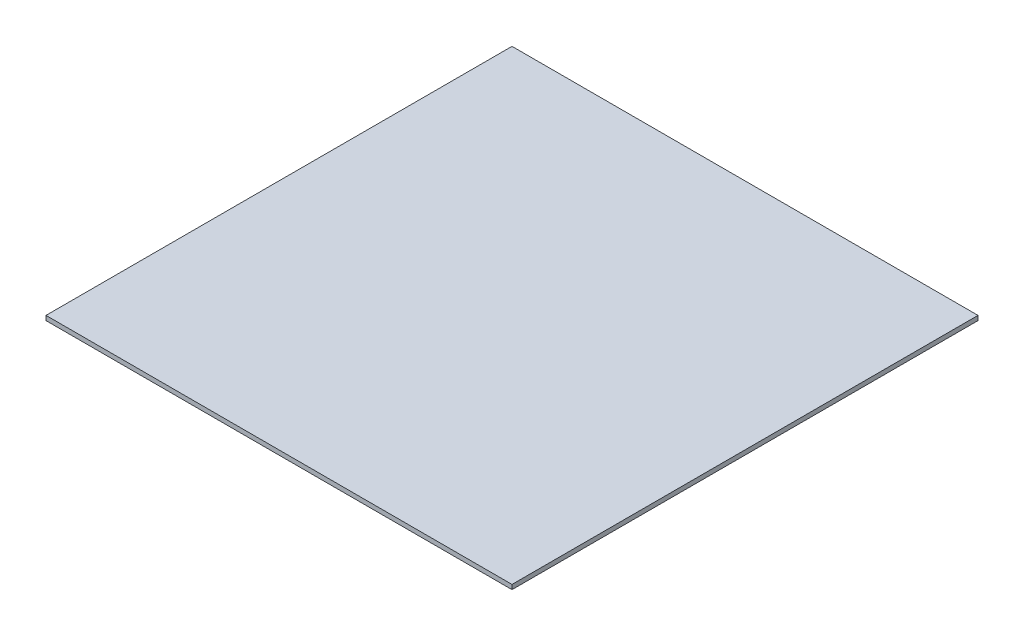
SolidWorks part; units mm, degrees
ref_plane "Front Plane" through (0, 0, 0) normal (0, 0, 1) x (1, 0, 0)
ref_plane "Top Plane" through (0, 0, 0) normal (0, 1, 0) x (1, 0, 0)
ref_plane "Right Plane" through (0, 0, 0) normal (1, 0, 0) x (0, 0, -1)
sketch "Sketch1" plane through (0, 0, 0) normal (0, 1, 0) x (1, 0, 0)
  line L1 (-205, -205) -> (205, -205)
  line L2 (-205, -205) -> (-205, 205)
  line L3 (-205, 205) -> (205, 205)
  line L4 (205, -205) -> (205, 205)
  line L5 (-205, -205) -> (205, 205) construction
  line L6 (-205, 205) -> (205, -205) construction
  point P0 (0, 0)
  dimension "D1" = 410
  dimension "D2" = 410
extrude "Boss-Extrude1" add sketch "Sketch1" along normal blind 4
